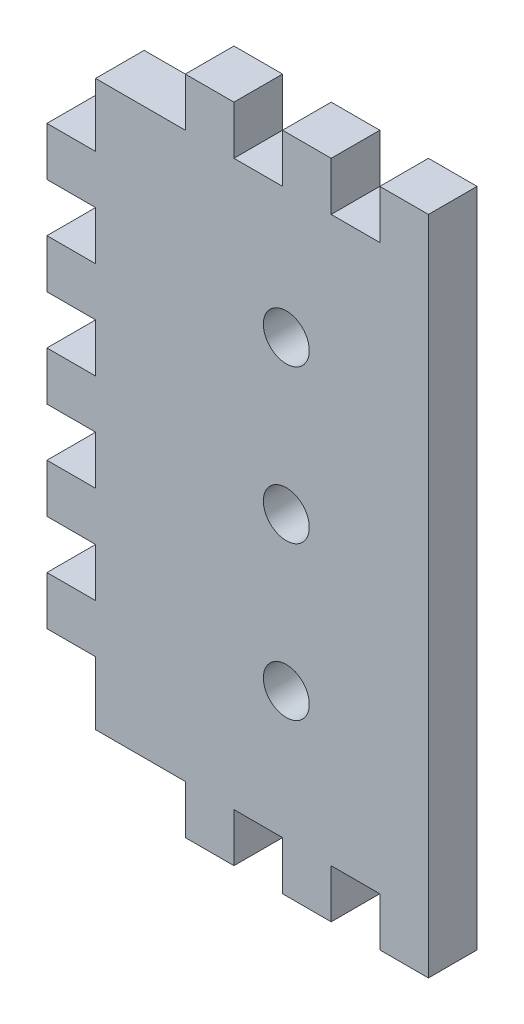
SolidWorks part; units mm, degrees
ref_plane "Front Plane" through (0, 0, 0) normal (0, 0, 1) x (1, 0, 0)
ref_plane "Top Plane" through (0, 0, 0) normal (0, 1, 0) x (1, 0, 0)
ref_plane "Right Plane" through (0, 0, 0) normal (1, 0, 0) x (0, 0, -1)
sketch "Sketch1" plane through (0, 0, 0) normal (0, 0, 1) x (1, 0, 0)
  line L1 (0, 0) -> (24.91, 0)
  line L2 (0, 0) -> (0, 40.005)
  line L3 (0, 40.005) -> (24.91, 40.005)
  line L4 (24.91, 0) -> (24.91, 40.005)
  dimension "D1" = 24.91
  dimension "D2" = 40.005
extrude "Boss-Extrude1" add sketch "Sketch1" along normal blind 3.175
sketch "Sketch4" plane through (0, 0, 3.175) normal (0, 0, 1) x (1, 0, 0)
  line L0 (0, 20.0025) -> (24.91, 20.0025) construction
  line L1 (0, 40.005) -> (0, 0) construction
  line L2 (24.91, 0) -> (24.91, 40.005) construction
sketch "Sketch7" plane through (0, 0, 0) normal (0, 0, -1) x (-1, 0, 0)
  line L0 (0, 40.005) -> (0, 0) construction
  line L1 (0, 32.7) -> (-3.175, 32.7)
  line L2 (0, 32.7) -> (0, 29.525)
  line L3 (0, 29.525) -> (-3.175, 29.525)
  line L4 (-3.175, 32.7) -> (-3.175, 29.525)
  line L5 (-24.91, 40.005) -> (0, 40.005) construction
  dimension "D1" = 3.175
  dimension "D2" = 3.175
  dimension "D3" = 7.305
extrude "Cut-Extrude5" cut sketch "Sketch7" against normal blind 3.175
pattern_linear "LPattern2" count 6 spacing 6.35 along (0, -1, 0) count 6 spacing 6.35 along (0, 1, 0) of "Cut-Extrude5"
sketch "Sketch8" plane through (0, 0, 0) normal (0, 0, -1) x (-1, 0, 0)
  line L1 (-3.175, 39.05) -> (0, 39.05)
  line L2 (-3.175, 39.05) -> (-3.175, 40.005)
  line L3 (-3.175, 40.005) -> (0, 40.005)
  line L4 (0, 39.05) -> (0, 40.005)
  line L5 (-3.175, 4.125) -> (0, 4.125)
  line L6 (-3.175, 4.125) -> (-3.175, 0.95)
  line L7 (-3.175, 0.95) -> (0, 0.95)
  line L8 (0, 4.125) -> (0, 0.95)
extrude "Cut-Extrude6" cut sketch "Sketch8" against normal blind 3.175
sketch "Sketch9" plane through (0, 0, 0) normal (0, 0, -1) x (-1, 0, 0)
  line L0 (-3.175, 0) -> (-24.91, 0) construction
  line L1 (-21.735, 0) -> (-18.56, 0)
  line L2 (-21.735, 0) -> (-21.735, 3.175)
  line L3 (-21.735, 3.175) -> (-18.56, 3.175)
  line L4 (-18.56, 0) -> (-18.56, 3.175)
  line L5 (-24.91, 0) -> (-24.91, 40.005) construction
  dimension "D1" = 3.175
  dimension "D2" = 3.175
  dimension "D3" = 3.175
extrude "Cut-Extrude7" cut sketch "Sketch9" against normal blind 3.175
pattern_linear "LPattern3" count 3 spacing 6.35 along (-1, 0, 0) of "Cut-Extrude7"
sketch "Sketch10" plane through (0, 0, 0) normal (0, 0, -1) x (-1, 0, 0)
  line L0 (-3.175, 7.3) -> (-3.175, 0) construction
  line L1 (-5.86, 0) -> (-3.175, 0)
  line L2 (-5.86, 0) -> (-5.86, 3.175)
  line L3 (-5.86, 3.175) -> (-3.175, 3.175)
  line L4 (-3.175, 0) -> (-3.175, 3.175)
extrude "Cut-Extrude8" cut sketch "Sketch10" against normal blind 3.175
sketch "Sketch12" plane through (0, 0, 0) normal (0, 0, -1) x (-1, 0, 0)
  line L1 (-24.91, 40.005) -> (-21.735, 40.005)
  line L2 (-24.91, 40.005) -> (-24.91, 43.18)
  line L3 (-24.91, 43.18) -> (-21.735, 43.18)
  line L4 (-21.735, 40.005) -> (-21.735, 43.18)
  dimension "D1" = 3.175
  dimension "D2" = 3.175
extrude "Boss-Extrude2" add sketch "Sketch12" against normal blind 3.175
sketch "Sketch13" plane through (0, 0, 0) normal (0, 0, -1) x (-1, 0, 0)
  line L0 (-24.91, 43.18) -> (-24.91, 0) construction
sketch "Sketch14" plane through (0, 0, 0) normal (0, 0, -1) x (-1, 0, 0)
  line L0 (-24.91, 21.59) -> (0, 21.5875) construction
  line L1 (-24.91, 43.18) -> (-24.91, 0) construction
  line L2 (0, 23.175) -> (0, 20) construction
pattern_linear "LPattern4" count 3 spacing 6.35 along (-1, 0, 0) of "Boss-Extrude2"
sketch "Sketch11" plane through (0, 0, 0) normal (0, 0, -1) x (-1, 0, 0)
  line L0 (-24.91, 0) -> (-24.91, 43.18) construction
  line L1 (-24.91, 21.59) -> (0, 21.5875) construction
  circle A0 centre (-15.63, 31.5891) radius 1.5
  dimension "D1" = 3
  dimension "D2" = 9.28
  dimension "D3" = 10
extrude "Cut-Extrude9" cut sketch "Sketch11" against normal blind 3.175
pattern_linear "LPattern5" count 3 spacing 10 along (0, -1, 0) of "Cut-Extrude9"
